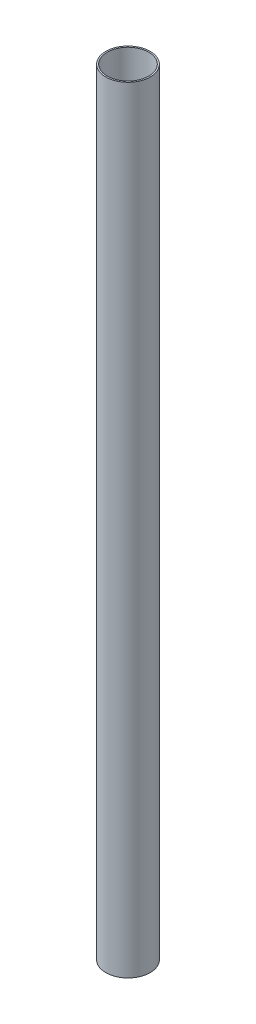
SolidWorks part; units mm, degrees
ref_plane "Alzado" through (0, 0, 0) normal (0, 0, 1) x (1, 0, 0)
ref_plane "Planta" through (0, 0, 0) normal (0, 1, 0) x (1, 0, 0)
ref_plane "Vista lateral" through (0, 0, 0) normal (1, 0, 0) x (0, 0, -1)
sketch "Croquis1" plane through (0, 0, 0) normal (0, 1, 0) x (1, 0, 0)
  circle A0 centre (0, 0) radius 21
  circle A1 centre (0, 0) radius 22.5
  dimension "D1" = 42
  dimension "D2" = 45
extrude "Saliente-Extruir1" add sketch "Croquis1" along normal blind 785
sketch "Croquis2" plane through (0, 0, 0) normal (0, 0, 1) x (1, 0, 0)
  line L0 (0, 0) -> (0, 785) construction
  line L1 (22.5, 785) -> (-22.5, 785) construction
  line L2 (-21, 0) -> (21, 0) construction
  line L3 (5, 160) -> (-5, 160)
  line L4 (5, 160) -> (5, 220)
  line L5 (5, 220) -> (-5, 220)
  line L6 (-5, 160) -> (-5, 220)
  point P11 (0, 160)
  dimension "D1" = 60
  dimension "D2" = 160
  dimension "D3" = 10
extrude "Cortar-Extruir1" cut sketch "Croquis2" against normal blind 785
